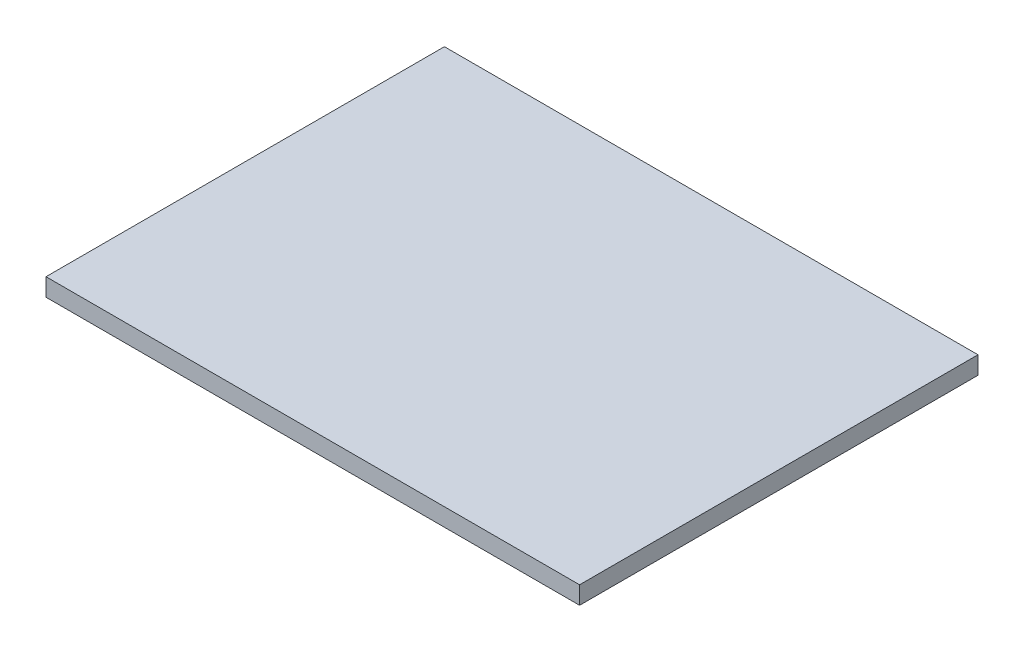
SolidWorks part; units mm, degrees
ref_plane "前视基准面" through (0, 0, 0) normal (0, 0, 1) x (1, 0, 0)
ref_plane "上视基准面" through (0, 0, 0) normal (0, 1, 0) x (1, 0, 0)
ref_plane "右视基准面" through (0, 0, 0) normal (1, 0, 0) x (0, 0, -1)
sketch "草图2" plane through (0, 0, 0) normal (0, 1, 0) x (1, 0, 0)
  line L1 (150, 112) -> (-150, 112)
  line L2 (150, 112) -> (150, -112)
  line L3 (150, -112) -> (-150, -112)
  line L4 (-150, 112) -> (-150, -112)
  line L5 (150, 112) -> (-150, -112) construction
  line L6 (150, -112) -> (-150, 112) construction
  point P0 (0, 0)
  dimension "D1" = 224
  dimension "D2" = 300
extrude "凸台-拉伸1" add sketch "草图2" along normal blind 10
sketch "草图3" plane through (0, 10, 0) normal (0, 1, 0) x (1, 0, 0)
  line L0 (-150, 0) -> (150, 0) construction
  line L1 (-150, 112) -> (-150, -112) construction
  line L2 (150, -112) -> (150, 112) construction
ref_plane "基准面1" through (0, 0, 0) normal (0, 0, -1) x (-1, 0, 0)
